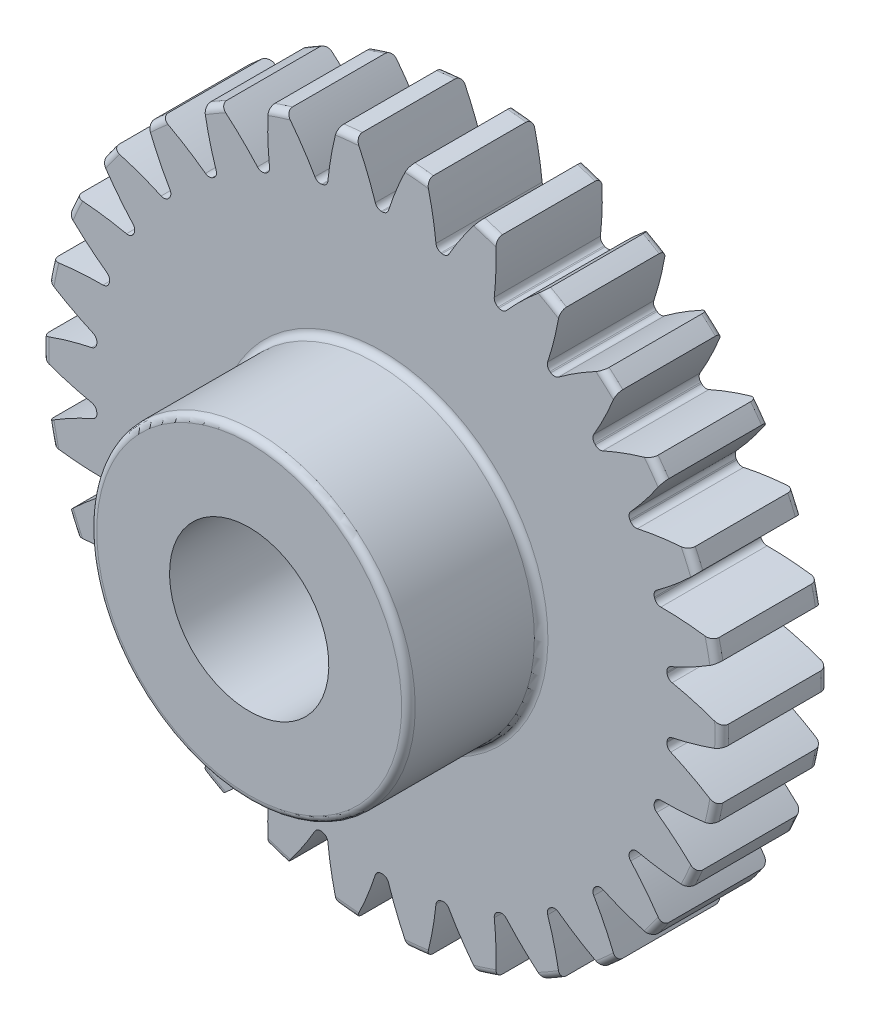
SolidWorks part; units mm, degrees
ref_plane "Front Plane" through (0, 0, 0) normal (0, 0, 1) x (1, 0, 0)
ref_plane "Top Plane" through (0, 0, 0) normal (0, 1, 0) x (1, 0, 0)
ref_plane "Right Plane" through (0, 0, 0) normal (1, 0, 0) x (0, 0, -1)
sketch "Sketch1" plane through (0, 0, 0) normal (0, 0, 1) x (1, 0, 0)
  line L0 (-381, 0) -> (381, 0) construction
  circle A0 centre (0, 0) radius 12.8 construction
  circle A1 centre (0, 0) radius 12 construction
  circle A2 centre (0, 0) radius 10.8 construction
  circle A3 centre (0, 0) radius 6 construction
  circle A4 centre (0, 0) radius 3 construction
  dimension "D1" = 2
  dimension "OD" = 25.6
  dimension "Pitch Dia." = 24
  dimension "D2" = 0.8
  dimension "D3" = 2
  dimension "Root Dia." = 21.6
  dimension "Hub Dia." = 12
  dimension "Shaft Dia." = 6
  dimension "Number of Teeth" = 762
sketch "Sketch2" plane through (0, 0, 0) normal (1, 0, 0) x (0, 0, -1)
  line L0 (0, 0) -> (-4, 0) construction
  line L1 (-4, 0) -> (-9, 0) construction
  dimension "Overall Width" = 9
  dimension "Face Width" = 4
sketch "Sketch4" plane through (0, 0, 0) normal (1, 0, 0) x (0, 0, -1)
  line L0 (-9, 3) -> (-9, 6)
  line L1 (-9, 6) -> (-4, 6)
  line L2 (-4, 6) -> (-4, 12.8)
  line L3 (-4, 12.8) -> (0, 12.8)
  line L4 (0, 12.8) -> (0, 3)
  line L5 (-4, 6) -> (-4, 0) construction
  line L6 (0, 12.8) -> (0, -12.8) construction
  line L7 (-4, 6) -> (0, 6) construction
  line L12 (-9, 3) -> (0, 3)
revolve "Revolve1" add sketch "Sketch4" angle 360 about L1
fillet "Fillet2" radius 0.256 4 edges at (0, 6, 9) (0, 6, 4) (0, 12.8, 4) (0, 12.8, 0)
sketch "Sketch7" plane through (0, 0, 4) normal (0, 0, 1) x (1, 0, 0)
  line L0 (0, 0) -> (0, 12.8) construction
  line L1 (0.628, 11.9836) -> (0.9593, 12.764) construction
  line L3 (1.338, 12.7299) -> (1.2543, 11.9343) construction
  line L4 (1.2543, 11.9343) -> (1.1289, 10.7408) construction
  line L5 (0, 0) -> (1.1289, 10.7408) construction
  line L6 (0.628, 11.9836) -> (0, 0) construction
  line L7 (0.628, 11.9836) -> (0.6699, 12.7825) construction
  line L8 (0.628, 11.9836) -> (0, 0) construction
  circle A0 centre (0, 0) radius 12.8 construction
  arc A1 (-0.0207, 10.8) -> (0.0207, 10.8) centre (0, 0) cw
  circle A2 centre (0, 0) radius 10.8 construction
  arc A3 (-0.628, 11.9836) -> (0.628, 11.9836) centre (0, 0) cw construction
  circle A4 centre (0, 0) radius 12 construction
  arc A5 (1.6833, 12.6888) -> (0.9916, 12.7615) centre (0, 0) ccw construction
  arc A6 (0.628, 11.9836) -> (1.8772, 11.8523) centre (0, 0) cw construction
  arc A7 (-0.9916, 12.7615) -> (0.9916, 12.7615) centre (0, 0) cw
  arc A8 (0.2496, 10.9666) -> (0.9916, 12.7615) centre (11.6741, 7.2948) cw
  arc A9 (-0.2496, 10.9666) -> (-0.9916, 12.7615) centre (-11.6741, 7.2948) ccw
  arc A10 (-0.0207, 10.8) -> (-0.2496, 10.9666) centre (-0.0211, 11.04) cw
  arc A11 (0.0207, 10.8) -> (0.2496, 10.9666) centre (0.0211, 11.04) ccw
  point P26 (-0.1969, 10.7982)
  point P29 (0.1969, 10.7982)
  dimension "D4" = 0.24
  dimension "D5" = 12
  dimension "D2" = 1.2566
  dimension "D1" = 2.5133
  dimension "D3" = 20
extrude "Cut-Extrude2" cut sketch "Sketch7" against normal through all
pattern_circular "CirPattern1" count 30 over 360 about axis through (0, 0, 0) along (0, 0, 1) of "Cut-Extrude2"
equation "\"D1@Sketch1\"=2.5*(\"Pitch Dia.@Sketch1\"/\"Number of Teeth@Sketch1\")"
equation "\"D1@CirPattern1\"=\"Number of Teeth@Sketch1\""
equation "\"D1@Fillet2\"=\"OD@Sketch1\"*.01"
equation "\"D1@Sketch7\"=3.14159*(\"Pitch Dia.@Sketch1\"/\"Number of Teeth@Sketch1\")"
equation "\"D2@Sketch7\"=\"D1@Sketch7\"/2"
equation "\"D4@Sketch7\"=\"D1@Sketch7\"*.0955"
equation "\"D5@Sketch7\"=\"Pitch Dia.@Sketch1\"/2"
